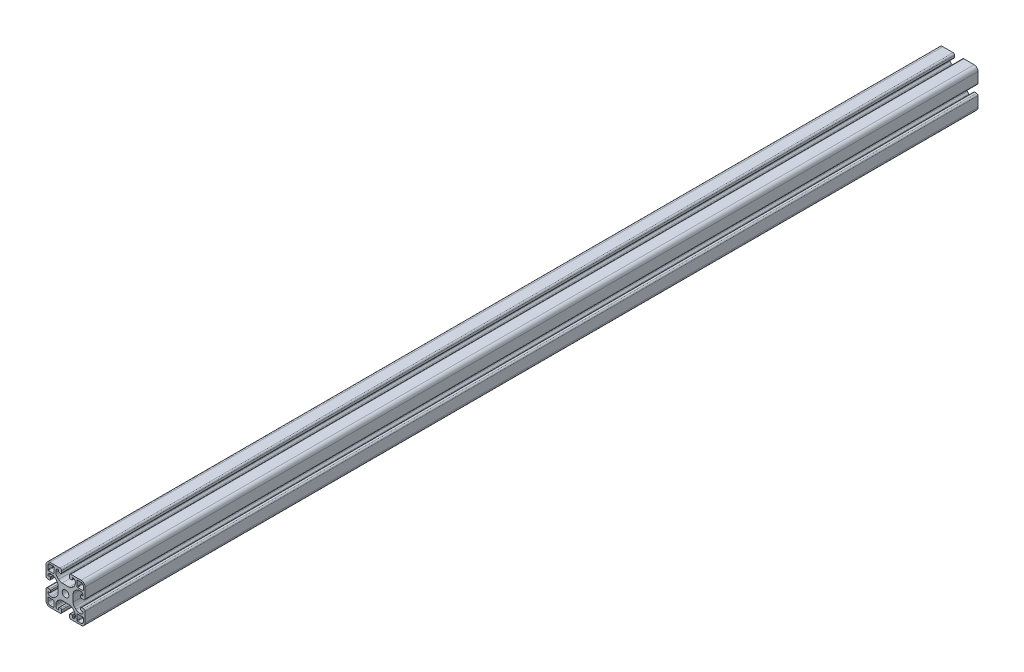
SolidWorks part; units mm, degrees
ref_plane "Plan de face" through (0, 0, 0) normal (0, 0, 1) x (1, 0, 0)
ref_plane "Plan de dessus" through (0, 0, 0) normal (0, 1, 0) x (1, 0, 0)
ref_plane "Plan de droite" through (0, 0, 0) normal (1, 0, 0) x (0, 0, -1)
ref_plane "Plan1" through (0, 0, -30) normal (0, 0, -1) x (-1, 0, 0)
sketch "Esquisse1" plane through (0, 0, -30) normal (0, 0, -1) x (-1, 0, 0)
  line L0 (-4.5, 15) -> (-4.5, 13.5)
  line L1 (-4, 13) -> (-2.5, 13)
  line L2 (-4.5, 10) -> (-5.8076, 10)
  line L3 (-9.3431, 11.4645) -> (-10.7855, 12.9069)
  line L4 (-12.25, 16.4424) -> (-12.25, 23.5576)
  line L5 (-10.7855, 27.0931) -> (-9.3431, 28.5355)
  line L6 (-5.8076, 30) -> (-4.5, 30)
  line L7 (-2.5, 27) -> (-4, 27)
  line L8 (-4.5, 26.5) -> (-4.5, 25)
  line L9 (-3.5, 24) -> (-1.5, 24)
  line L10 (0, 25.5) -> (0, 36)
  line L11 (-4, 40) -> (-14.5, 40)
  line L12 (-16, 38.5) -> (-16, 36.5)
  line L13 (-15, 35.5) -> (-13.5, 35.5)
  line L14 (-13, 36) -> (-13, 37.5)
  line L15 (-10, 35.5) -> (-10, 34.1924)
  line L16 (-11.4645, 30.6569) -> (-12.9069, 29.2145)
  line L17 (-16.4424, 27.75) -> (-23.5576, 27.75)
  line L18 (-27.0931, 29.2145) -> (-28.5355, 30.6569)
  line L19 (-30, 34.1924) -> (-30, 35.5)
  line L20 (-27, 37.5) -> (-27, 36)
  line L21 (-26.5, 35.5) -> (-25, 35.5)
  line L22 (-24, 36.5) -> (-24, 38.5)
  line L23 (-25.5, 40) -> (-36, 40)
  line L24 (-40, 36) -> (-40, 25.5)
  line L25 (-38.5, 24) -> (-36.5, 24)
  line L26 (-35.5, 25) -> (-35.5, 26.5)
  line L27 (-36, 27) -> (-37.5, 27)
  line L28 (-35.5, 30) -> (-34.1924, 30)
  line L29 (-30.6569, 28.5355) -> (-29.2145, 27.0931)
  line L30 (-27.75, 23.5576) -> (-27.75, 16.4424)
  line L31 (-29.2145, 12.9069) -> (-30.6569, 11.4645)
  line L32 (-34.1924, 10) -> (-35.5, 10)
  line L33 (-37.5, 13) -> (-36, 13)
  line L34 (-35.5, 13.5) -> (-35.5, 15)
  line L35 (-36.5, 16) -> (-38.5, 16)
  line L36 (-40, 14.5) -> (-40, 4)
  line L37 (-36, 0) -> (-25.5, 0)
  line L38 (-24, 1.5) -> (-24, 3.5)
  line L39 (-25, 4.5) -> (-26.5, 4.5)
  line L40 (-27, 4) -> (-27, 2.5)
  line L41 (-30, 4.5) -> (-30, 5.8076)
  line L42 (-28.5355, 9.3431) -> (-27.0931, 10.7855)
  line L43 (-23.5576, 12.25) -> (-16.4424, 12.25)
  line L44 (-12.9069, 10.7855) -> (-11.4645, 9.3431)
  line L45 (-10, 5.8076) -> (-10, 4.5)
  line L46 (-13, 2.5) -> (-13, 4)
  line L47 (-13.5, 4.5) -> (-15, 4.5)
  line L48 (-16, 3.5) -> (-16, 1.5)
  line L49 (-14.5, 0) -> (-4, 0)
  line L50 (0, 4) -> (0, 14.5)
  line L51 (-1.5, 16) -> (-3.5, 16)
  line L52 (-4, 1.8) -> (-7.7, 1.8)
  line L53 (-8.2, 2.3) -> (-8.2, 7.7)
  line L54 (-7.7, 8.2) -> (-2.3, 8.2)
  line L55 (-1.8, 7.7) -> (-1.8, 4)
  line L56 (-38.2, 4) -> (-38.2, 7.7)
  line L57 (-37.7, 8.2) -> (-32.3, 8.2)
  line L58 (-31.8, 7.7) -> (-31.8, 2.3)
  line L59 (-32.3, 1.8) -> (-36, 1.8)
  line L60 (-36, 38.2) -> (-32.3, 38.2)
  line L61 (-31.8, 37.7) -> (-31.8, 32.3)
  line L62 (-32.3, 31.8) -> (-37.7, 31.8)
  line L63 (-38.2, 32.3) -> (-38.2, 36)
  line L64 (-1.8, 36) -> (-1.8, 32.3)
  line L65 (-2.3, 31.8) -> (-7.7, 31.8)
  line L66 (-8.2, 32.3) -> (-8.2, 37.7)
  line L67 (-7.7, 38.2) -> (-4, 38.2)
  arc A0 (-4.5, 13.5) -> (-4, 13) centre (-4, 13.5) ccw
  arc A1 (-2.5, 13) -> (-2, 12.5) centre (-2.5, 12.5) cw
  arc A2 (-2, 12.5) -> (-4.5, 10) centre (-4.5, 12.5) cw
  arc A3 (-5.8076, 10) -> (-9.3431, 11.4645) centre (-5.8076, 15) cw
  arc A4 (-10.7855, 12.9069) -> (-12.25, 16.4424) centre (-7.25, 16.4424) cw
  arc A5 (-12.25, 23.5576) -> (-10.7855, 27.0931) centre (-7.25, 23.5576) cw
  arc A6 (-9.3431, 28.5355) -> (-5.8076, 30) centre (-5.8076, 25) cw
  arc A7 (-4.5, 30) -> (-2, 27.5) centre (-4.5, 27.5) cw
  arc A8 (-2, 27.5) -> (-2.5, 27) centre (-2.5, 27.5) cw
  arc A9 (-4, 27) -> (-4.5, 26.5) centre (-4, 26.5) ccw
  arc A10 (-4.5, 25) -> (-3.5, 24) centre (-3.5, 25) ccw
  arc A11 (-1.5, 24) -> (0, 25.5) centre (-1.5, 25.5) ccw
  arc A12 (0, 36) -> (-4, 40) centre (-4, 36) ccw
  arc A13 (-14.5, 40) -> (-16, 38.5) centre (-14.5, 38.5) ccw
  arc A14 (-16, 36.5) -> (-15, 35.5) centre (-15, 36.5) ccw
  arc A15 (-13.5, 35.5) -> (-13, 36) centre (-13.5, 36) ccw
  arc A16 (-13, 37.5) -> (-12.5, 38) centre (-12.5, 37.5) cw
  arc A17 (-12.5, 38) -> (-10, 35.5) centre (-12.5, 35.5) cw
  arc A18 (-10, 34.1924) -> (-11.4645, 30.6569) centre (-15, 34.1924) cw
  arc A19 (-12.9069, 29.2145) -> (-16.4424, 27.75) centre (-16.4424, 32.75) cw
  arc A20 (-23.5576, 27.75) -> (-27.0931, 29.2145) centre (-23.5576, 32.75) cw
  arc A21 (-28.5355, 30.6569) -> (-30, 34.1924) centre (-25, 34.1924) cw
  arc A22 (-30, 35.5) -> (-27.5, 38) centre (-27.5, 35.5) cw
  arc A23 (-27.5, 38) -> (-27, 37.5) centre (-27.5, 37.5) cw
  arc A24 (-27, 36) -> (-26.5, 35.5) centre (-26.5, 36) ccw
  arc A25 (-25, 35.5) -> (-24, 36.5) centre (-25, 36.5) ccw
  arc A26 (-24, 38.5) -> (-25.5, 40) centre (-25.5, 38.5) ccw
  arc A27 (-36, 40) -> (-40, 36) centre (-36, 36) ccw
  arc A28 (-40, 25.5) -> (-38.5, 24) centre (-38.5, 25.5) ccw
  arc A29 (-36.5, 24) -> (-35.5, 25) centre (-36.5, 25) ccw
  arc A30 (-35.5, 26.5) -> (-36, 27) centre (-36, 26.5) ccw
  arc A31 (-37.5, 27) -> (-38, 27.5) centre (-37.5, 27.5) cw
  arc A32 (-38, 27.5) -> (-35.5, 30) centre (-35.5, 27.5) cw
  arc A33 (-34.1924, 30) -> (-30.6569, 28.5355) centre (-34.1924, 25) cw
  arc A34 (-29.2145, 27.0931) -> (-27.75, 23.5576) centre (-32.75, 23.5576) cw
  arc A35 (-27.75, 16.4424) -> (-29.2145, 12.9069) centre (-32.75, 16.4424) cw
  arc A36 (-30.6569, 11.4645) -> (-34.1924, 10) centre (-34.1924, 15) cw
  arc A37 (-35.5, 10) -> (-38, 12.5) centre (-35.5, 12.5) cw
  arc A38 (-38, 12.5) -> (-37.5, 13) centre (-37.5, 12.5) cw
  arc A39 (-36, 13) -> (-35.5, 13.5) centre (-36, 13.5) ccw
  arc A40 (-35.5, 15) -> (-36.5, 16) centre (-36.5, 15) ccw
  arc A41 (-38.5, 16) -> (-40, 14.5) centre (-38.5, 14.5) ccw
  arc A42 (-40, 4) -> (-36, 0) centre (-36, 4) ccw
  arc A43 (-25.5, 0) -> (-24, 1.5) centre (-25.5, 1.5) ccw
  arc A44 (-24, 3.5) -> (-25, 4.5) centre (-25, 3.5) ccw
  arc A45 (-26.5, 4.5) -> (-27, 4) centre (-26.5, 4) ccw
  arc A46 (-27, 2.5) -> (-27.5, 2) centre (-27.5, 2.5) cw
  arc A47 (-27.5, 2) -> (-30, 4.5) centre (-27.5, 4.5) cw
  arc A48 (-30, 5.8076) -> (-28.5355, 9.3431) centre (-25, 5.8076) cw
  arc A49 (-27.0931, 10.7855) -> (-23.5576, 12.25) centre (-23.5576, 7.25) cw
  arc A50 (-16.4424, 12.25) -> (-12.9069, 10.7855) centre (-16.4424, 7.25) cw
  arc A51 (-11.4645, 9.3431) -> (-10, 5.8076) centre (-15, 5.8076) cw
  arc A52 (-10, 4.5) -> (-12.5, 2) centre (-12.5, 4.5) cw
  arc A53 (-12.5, 2) -> (-13, 2.5) centre (-12.5, 2.5) cw
  arc A54 (-13, 4) -> (-13.5, 4.5) centre (-13.5, 4) ccw
  arc A55 (-15, 4.5) -> (-16, 3.5) centre (-15, 3.5) ccw
  arc A56 (-16, 1.5) -> (-14.5, 0) centre (-14.5, 1.5) ccw
  arc A57 (-4, 0) -> (0, 4) centre (-4, 4) ccw
  arc A58 (0, 14.5) -> (-1.5, 16) centre (-1.5, 14.5) ccw
  arc A59 (-3.5, 16) -> (-4.5, 15) centre (-3.5, 15) ccw
  circle A60 centre (-20, 20) radius 3.4
  arc A61 (-1.8, 4) -> (-4, 1.8) centre (-4, 4) cw
  arc A62 (-7.7, 1.8) -> (-8.2, 2.3) centre (-7.7, 2.3) cw
  arc A63 (-8.2, 7.7) -> (-7.7, 8.2) centre (-7.7, 7.7) cw
  arc A64 (-2.3, 8.2) -> (-1.8, 7.7) centre (-2.3, 7.7) cw
  arc A65 (-36, 1.8) -> (-38.2, 4) centre (-36, 4) cw
  arc A66 (-38.2, 7.7) -> (-37.7, 8.2) centre (-37.7, 7.7) cw
  arc A67 (-32.3, 8.2) -> (-31.8, 7.7) centre (-32.3, 7.7) cw
  arc A68 (-31.8, 2.3) -> (-32.3, 1.8) centre (-32.3, 2.3) cw
  arc A69 (-38.2, 36) -> (-36, 38.2) centre (-36, 36) cw
  arc A70 (-32.3, 38.2) -> (-31.8, 37.7) centre (-32.3, 37.7) cw
  arc A71 (-31.8, 32.3) -> (-32.3, 31.8) centre (-32.3, 32.3) cw
  arc A72 (-37.7, 31.8) -> (-38.2, 32.3) centre (-37.7, 32.3) cw
  arc A73 (-4, 38.2) -> (-1.8, 36) centre (-4, 36) cw
  arc A74 (-1.8, 32.3) -> (-2.3, 31.8) centre (-2.3, 32.3) cw
  arc A75 (-7.7, 31.8) -> (-8.2, 32.3) centre (-7.7, 32.3) cw
  arc A76 (-8.2, 37.7) -> (-7.7, 38.2) centre (-7.7, 37.7) cw
extrude "Boss.-Extru.1" add sketch "Esquisse1" against normal blind 915
